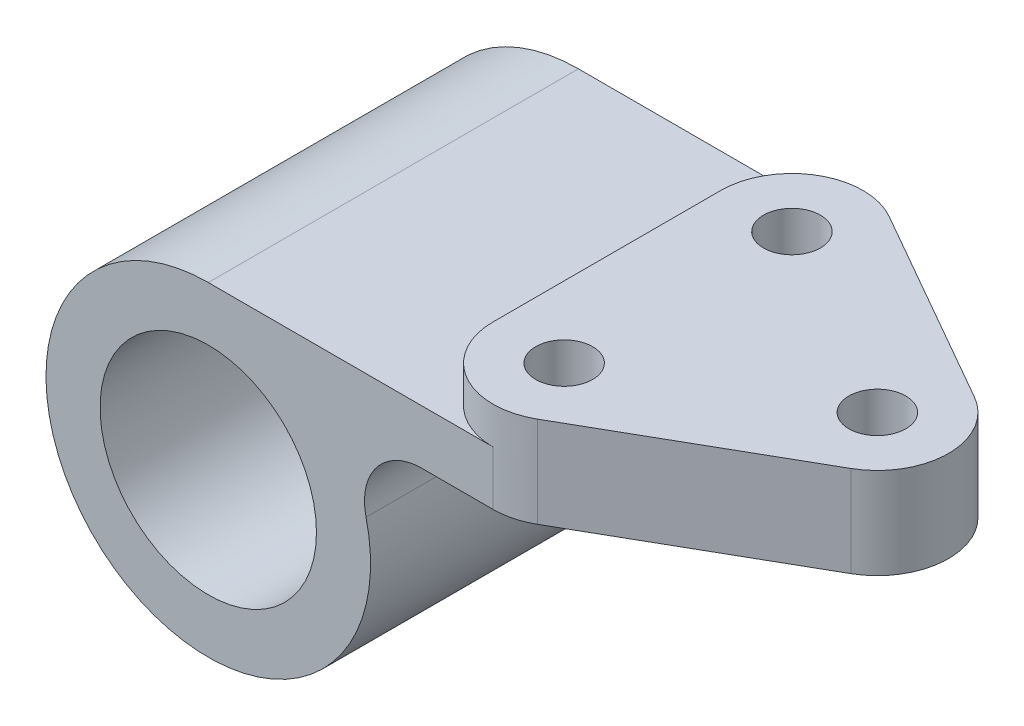
SolidWorks part; units mm, degrees
ref_plane "Front Plane" through (0, 0, 0) normal (0, 0, 1) x (1, 0, 0)
ref_plane "Top Plane" through (0, 0, 0) normal (0, 1, 0) x (1, 0, 0)
ref_plane "Right Plane" through (0, 0, 0) normal (1, 0, 0) x (0, 0, -1)
sketch "Sketch1" plane through (0, 0, 0) normal (0, 0, 1) x (1, 0, 0)
  line L0 (37.4333, 19) -> (50, 19)
  line L2 (50, 19) -> (50, 28.5)
  line L3 (0, 28.5) -> (50, 28.5)
  line L4 (0, 0) -> (0, 28.5) construction
  line L5 (21.2426, 19) -> (0, 19) construction
  arc A0 (0, 28.5) -> (27.7103, 6.6623) centre (0, 0) ccw
  circle A1 centre (0, 0) radius 19
  arc A2 (37.4333, 19) -> (27.7103, 6.6623) centre (37.4333, 9) ccw
  dimension "D2" = 57
  dimension "D3" = 38
  dimension "D4" = 10
  dimension "D1" = 50
extrude "Boss-Extrude1" add sketch "Sketch1" along normal mid plane 65
sketch "Sketch2" plane through (0, 28.5, 0) normal (0, 1, 0) x (1, 0, 0)
  line L4 (50, -32.5) -> (50, 32.5) construction
  line L6 (37.5, 20) -> (37.5, -20)
  line L9 (50, -32.5) -> (0, -32.5) construction
  line L12 (50, 0) -> (85, 0) construction
  line L13 (56.2017, 30.853) -> (91.2017, 10.853)
  line L14 (56.2017, -30.853) -> (91.2017, -10.853)
  line L15 (50, 32.5) -> (0, 32.5) construction
  arc A7 (56.2017, 30.853) -> (37.5, 20) centre (50, 20) ccw
  arc A8 (37.5, -20) -> (56.2017, -30.853) centre (50, -20) ccw
  arc A9 (91.2017, -10.853) -> (91.2017, 10.853) centre (85, 0) ccw
  circle A10 centre (50, 20) radius 5
  circle A11 centre (50, -20) radius 5
  circle A12 centre (85, 0) radius 5
  point P4 (50, 0)
  dimension "D2" = 12.5
  dimension "D3" = 12.5
  dimension "D5" = 10
  dimension "D1" = 35
  dimension "D4" = 40
extrude "Boss-Extrude2" add sketch "Sketch2" along normal blind 16 from surface at -9.5 starting at face at (43.7166, 19, 0)
sketch "Sketch4" plane through (0, 35, 0) normal (0, 1, 0) x (1, 0, 0)
  line L3 (56.2017, -30.853) -> (91.2017, -10.853)
  line L4 (91.2017, 10.853) -> (56.2017, 30.853)
  line L5 (37.5, 20) -> (37.5, -20)
  line L6 (56.2017, -30.853) -> (91.2017, -10.853)
  line L7 (91.2017, 10.853) -> (56.2017, 30.853)
  line L8 (37.5, 20) -> (37.5, -20)
  arc A3 (91.2017, -10.853) -> (91.2017, 10.853) centre (85, 0) ccw
  arc A4 (56.2017, 30.853) -> (37.5, 20) centre (50, 20) ccw
  arc A5 (37.5, -20) -> (56.2017, -30.853) centre (50, -20) ccw
  arc A6 (91.2017, -10.853) -> (91.2017, 10.853) centre (85, 0) ccw
  arc A7 (56.2017, 30.853) -> (37.5, 20) centre (50, 20) ccw
  arc A8 (37.5, -20) -> (56.2017, -30.853) centre (50, -20) ccw
  circle M7 centre (50, 20) radius 5
  circle M14 centre (50, -20) radius 5
  circle M15 centre (85, 0) radius 5
  dimension "D1" = 0
extrude "Cut-Extrude2" cut sketch "Sketch4" against normal blind 16 contours M14 | M15 | M7
equation "\"D2@Sketch1\"=28.5*2"
